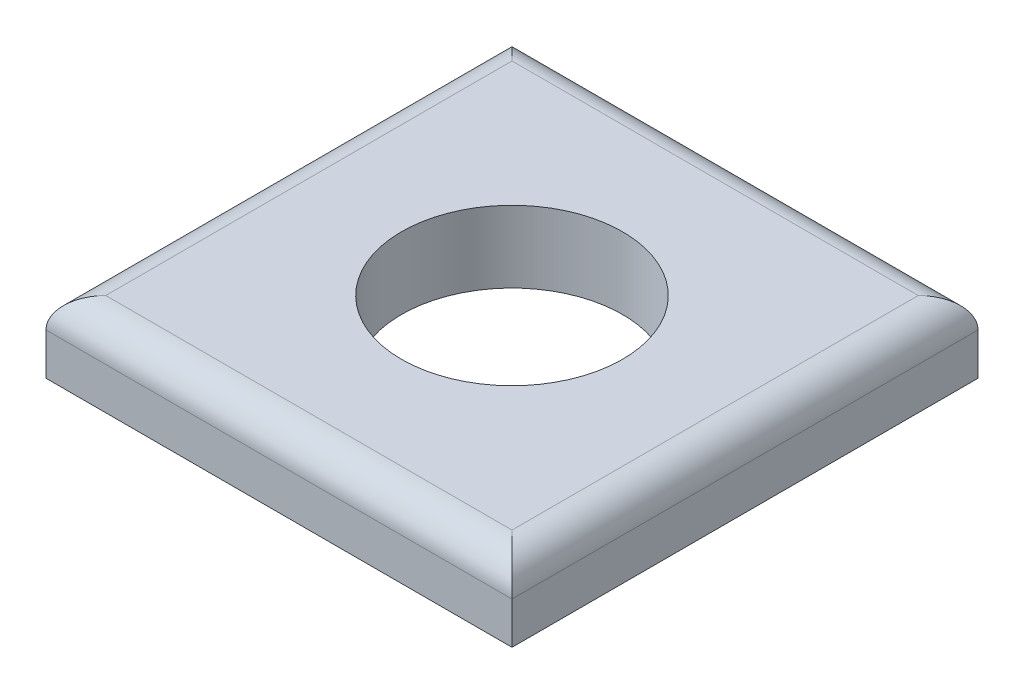
SolidWorks part; units mm, degrees
ref_plane "前视基准面" through (0, 0, 0) normal (0, 0, 1) x (1, 0, 0)
ref_plane "上视基准面" through (0, 0, 0) normal (0, 1, 0) x (1, 0, 0)
ref_plane "右视基准面" through (0, 0, 0) normal (1, 0, 0) x (0, 0, -1)
sketch "草图1" plane through (0, 0, 0) normal (0, 1, 0) x (1, 0, 0)
  line L0 (-14.6896, 0) -> (12.7218, 0) construction
  line L1 (-3.9, 3.9) -> (3.9, 3.9)
  line L2 (-3.9, 3.9) -> (-3.9, -3.9)
  line L3 (-3.9, -3.9) -> (3.9, -3.9)
  line L4 (3.9, 3.9) -> (3.9, -3.9)
  line L5 (0, 7.9866) -> (0, -8.1972) construction
  dimension "D1" = 7.8
  dimension "D2" = 7.8
extrude "拉伸1" add sketch "草图1" along normal blind 1.2
sketch "草图2" plane through (0, 1.2, 0) normal (0, 1, 0) x (-1, 0, 0)
  circle A0 centre (0, 0) radius 1.85
  dimension "D1" = 3.7
extrude "切除-拉伸1" cut sketch "草图2" against normal blind 1.2
fillet "圆角1" radius 0.5 4 edges at (0, 1.2, 3.9) (3.9, 1.2, 0) (0, 1.2, -3.9) (-3.9, 1.2, 0)
